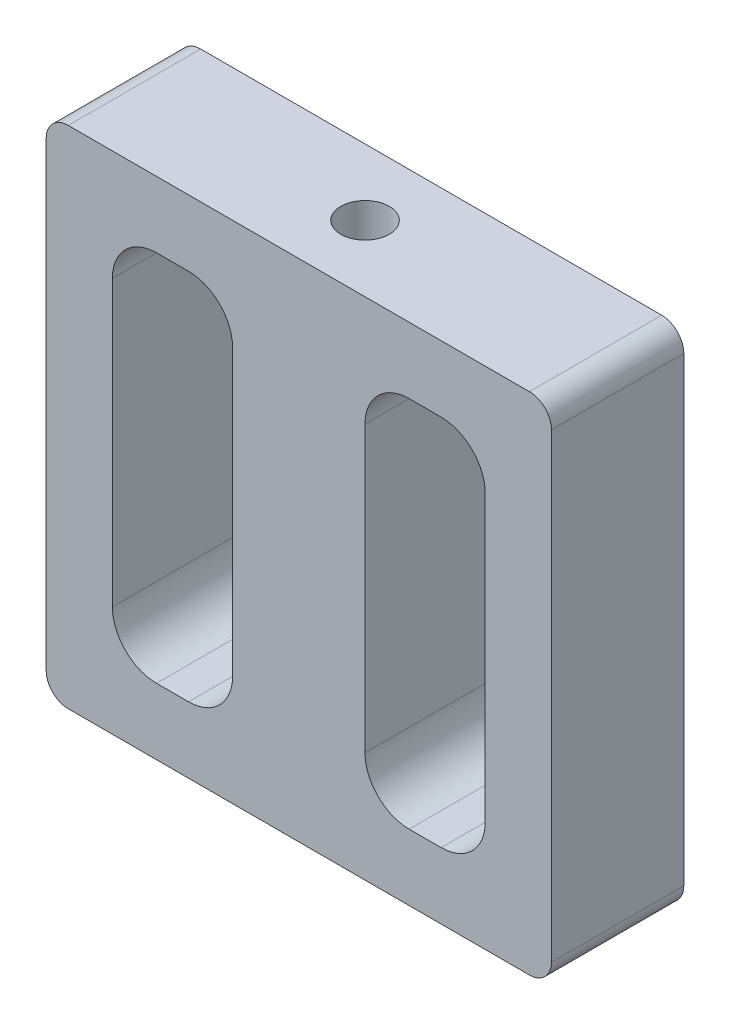
SolidWorks part; units mm, degrees
material "PLA"
ref_plane "前视基准面" through (0, 0, 0) normal (0, 0, 1) x (1, 0, 0)
ref_plane "上视基准面" through (0, 0, 0) normal (0, 1, 0) x (1, 0, 0)
ref_plane "右视基准面" through (0, 0, 0) normal (1, 0, 0) x (0, 0, -1)
sketch "草图1" plane through (0, 0, 0) normal (0, 0, 1) x (1, 0, 0)
  line L1 (11.45, -11.45) -> (-11.45, -11.45)
  line L2 (11.45, -11.45) -> (11.45, 11.45)
  line L3 (11.45, 11.45) -> (-11.45, 11.45)
  line L4 (-11.45, -11.45) -> (-11.45, 11.45)
  line L5 (11.45, -11.45) -> (-11.45, 11.45) construction
  line L6 (11.45, 11.45) -> (-11.45, -11.45) construction
  point P0 (0, 0)
  dimension "D1" = 22.9
extrude "凸台-拉伸1" add sketch "草图1" along normal blind 6
sketch "草图2" plane through (0, 11.45, 0) normal (0, 1, 0) x (1, 0, 0)
  line L0 (11.45, -3) -> (7.4072, -3) construction
  line L1 (11.45, -6) -> (11.45, 0) construction
  circle A0 centre (0, -3) radius 1.1
  dimension "D1" = 2.2
extrude "切除-拉伸1" cut sketch "草图2" against normal through all
sketch "草图3" plane through (0, 0, 0) normal (0, 0, -1) x (-1, 0, 0)
  line L0 (0, 0) -> (0, -6.9295) construction
  line L1 (3, 8.45) -> (8.45, 8.45)
  line L2 (3, 8.45) -> (3, -8.45)
  line L3 (3, -8.45) -> (8.45, -8.45)
  line L4 (8.45, 8.45) -> (8.45, -8.45)
  line L5 (3, 8.45) -> (8.45, -8.45) construction
  line L6 (3, -8.45) -> (8.45, 8.45) construction
  line L7 (-3, -8.45) -> (-8.45, -8.45)
  line L8 (-8.45, 8.45) -> (-8.45, -8.45)
  line L9 (-3, 8.45) -> (-8.45, 8.45)
  line L10 (-3, 8.45) -> (-3, -8.45)
  line L11 (-11.45, -11.45) -> (-11.45, 11.45) construction
  line L12 (11.45, -11.45) -> (-11.45, -11.45) construction
  line L13 (-11.45, 11.45) -> (11.45, 11.45) construction
  point P0 (5.725, 0)
  dimension "D1" = 6
  dimension "D2" = 3
  dimension "D3" = 3
  dimension "D4" = 3
extrude "切除-拉伸2" cut sketch "草图3" against normal blind 6
fillet "圆角1" radius 2 8 edges at (8.45, 8.45, 3) (8.45, -8.45, 3) (3, -8.45, 3) (3, 8.45, 3) (-3, 8.45, 3) (-8.45, 8.45, 3) (-3, -8.45, 3) (-8.45, -8.45, 3)
fillet "圆角2" radius 1 4 edges at (-11.45, 11.45, 3) (11.45, 11.45, 3) (11.45, -11.45, 3) (-11.45, -11.45, 3)
